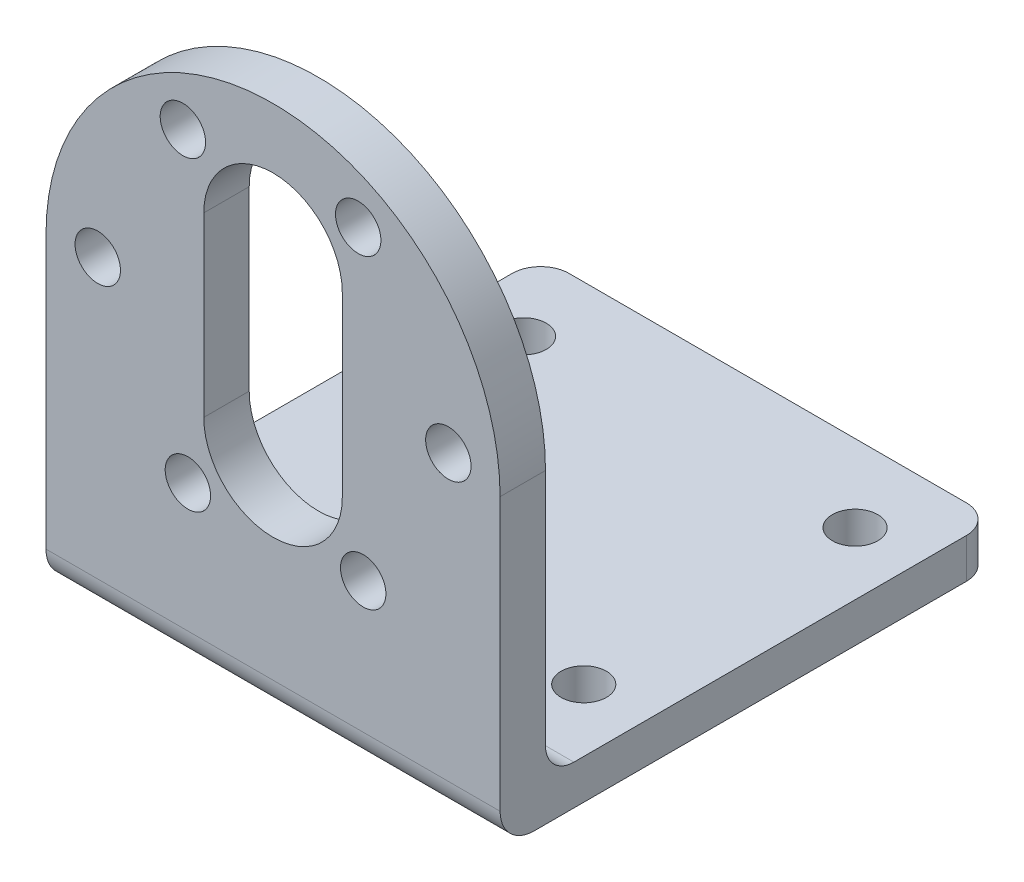
SolidWorks part; units mm, degrees
ref_plane "Front Plane" through (0, 0, 0) normal (0, 0, 1) x (1, 0, 0)
ref_plane "Top Plane" through (0, 0, 0) normal (0, 1, 0) x (1, 0, 0)
ref_plane "Right Plane" through (0, 0, 0) normal (1, 0, 0) x (0, 0, -1)
sketch "Sketch2" plane through (0, 0, 0) normal (1, 0, 0) x (0, 0, -1)
  line L1 (-36.8894, 36.5355) -> (-35.3894, 36.5355)
  line L2 (-36.8894, 36.5355) -> (-36.8894, -2.5345)
  line L3 (-36.8894, -2.5345) -> (-35.3894, -2.5345)
  line L4 (-35.3894, 36.5355) -> (-35.3894, -2.5345)
  line L5 (-36.8894, -2.5345) -> (4.1796, -2.5345)
  line L6 (-36.8894, -2.5345) -> (-36.8894, -1.0345)
  line L7 (-36.8894, -1.0345) -> (4.1796, -1.0345)
  line L8 (4.1796, -2.5345) -> (4.1796, -1.0345)
  dimension "D1" = 1.5
  dimension "D2" = 1.5
  dimension "D3" = 39.07
  dimension "D4" = 41.069
extrude "Boss-Extrude1" add sketch "Sketch2" along normal blind 40 contours L3 L4 L1 L2 | L5 L8 L7 L6
sketch "Sketch3" plane through (0, -1.0345, 0) normal (0, 1, 0) x (1, 0, 0)
  line L0 (40, 4.1796) -> (0, 4.1796) construction
  line L1 (0, -35.3894) -> (0, 4.1796) construction
  line L2 (40, -35.3894) -> (40, 4.1796) construction
  circle A0 centre (4.5, -30.8204) radius 1.65
  circle A1 centre (4.5, -20.8204) radius 1.65
  circle A2 centre (4.5, -10.8204) radius 1.65
  circle A3 centre (4.5, -0.8204) radius 1.65
  circle A4 centre (35.5, -30.8204) radius 1.65
  circle A5 centre (35.5, -20.8204) radius 1.65
  circle A6 centre (35.5, -10.8204) radius 1.65
  circle A7 centre (35.5, -0.8204) radius 1.65
  dimension "D1" = 3.3
  dimension "D2" = 5
  dimension "D3" = 10
  dimension "D4" = 10
  dimension "D5" = 10
  dimension "D6" = 5
  dimension "D7" = 10
  dimension "D8" = 10
  dimension "D9" = 30
  dimension "D10" = 4.5
  dimension "D11" = 4.5
  dimension "D12" = 4.5
  dimension "D13" = 4.5
  dimension "D14" = 4.5
  dimension "D15" = 4.5
extrude "Cut-Extrude1" cut sketch "Sketch3" against normal blind 40
sketch "Sketch4" plane through (0, 0, 35.3894) normal (0, 0, -1) x (-1, 0, 0)
  circle A0 centre (-20, 16.5355) radius 10.5
  circle A1 centre (-20, 16.5355) radius 13
  circle A2 centre (-29.4484, 25.4645) radius 1.65
  circle A3 centre (-10.5516, 7.6065) radius 1.65
  circle A4 centre (-28.929, 7.0871) radius 1.65
  circle A5 centre (-11.071, 25.984) radius 1.65
  arc A6 (-40, 16.5355) -> (0, 16.5355) centre (-20, 16.5355) cw
  line M2 (0, -1.0345) -> (0, 36.5355)
  line M3 (0, 36.5355) -> (-40, 36.5355)
  line M4 (-40, 36.5355) -> (-40, -1.0345)
  dimension "D1" = 21
  dimension "D4" = 26
  dimension "D5" = 3.3
  dimension "D9" = 20
  dimension "D2" = 19.07
  dimension "D3" = 20
  dimension "D6" = 90
  dimension "D7" = 90
  dimension "D8" = 90
  dimension "D10" = 40
extrude "Cut-Extrude2" cut sketch "Sketch4" against normal blind 40 contours A0 | A1 A4 | A1 A4 | A1 A3 | A1 A3 | A6 M4 M3 | A6 M3 M2 | A1 A5 | A1 A5 | A1 A2 | A1 A2
sketch "草图1" plane through (0, 0, 36.8894) normal (0, 0, 1) x (1, 0, 0)
  line L3 (0, 16.5355) -> (0, -2.5345)
  line L4 (0, -2.5345) -> (40, -2.5345)
  line L5 (40, -2.5345) -> (40, 16.5355)
  line L6 (0, 16.5355) -> (0, -2.5345)
  line L7 (0, -2.5345) -> (40, -2.5345)
  line L8 (40, -2.5345) -> (40, 16.5355)
  circle A0 centre (20, 16.5355) radius 10.5 construction
  arc A1 (40, 16.5355) -> (0, 16.5355) centre (20, 16.5355) ccw
  arc A2 (40, 16.5355) -> (0, 16.5355) centre (20, 16.5355) ccw
  circle A3 centre (20, 16.5355) radius 10.5
  circle A4 centre (11.071, 25.984) radius 1.65 construction
  circle A5 centre (29.4484, 25.4645) radius 1.65 construction
  circle A6 centre (28.929, 7.0871) radius 1.65 construction
  circle A7 centre (10.5516, 7.6065) radius 1.65 construction
  circle A8 centre (11.071, 25.984) radius 1.65
  circle A9 centre (29.4484, 25.4645) radius 1.65
  circle A10 centre (28.929, 7.0871) radius 1.65
  circle A11 centre (10.5516, 7.6065) radius 1.65
  dimension "D1" = 0
extrude "凸台-拉伸1" add sketch "草图1" along normal blind 2.5
fillet "圆角1" radius 2.5 1 edges at (20, -1.0345, 35.3894)
sketch "草图2" plane through (0, -2.5345, 0) normal (0, -1, 0) x (1, 0, 0)
  line L1 (40, 39.3894) -> (0, 39.3894)
  line L2 (40, 39.3894) -> (40, -4.1796)
  line L3 (40, -4.1796) -> (0, -4.1796)
  line L4 (0, 39.3894) -> (0, -4.1796)
  circle A0 centre (4.5, 30.8204) radius 1.65
  circle A1 centre (4.5, 20.8204) radius 1.65
  circle A2 centre (4.5, 0.8204) radius 1.65
  circle A3 centre (4.5, 10.8204) radius 1.65
  circle A4 centre (35.5, 30.8204) radius 1.65
  circle A5 centre (35.5, 20.8204) radius 1.65
  circle A6 centre (35.5, 10.8204) radius 1.65
  circle A7 centre (35.5, 0.8204) radius 1.65
extrude "凸台-拉伸2" add sketch "草图2" along normal blind 2
fillet "圆角2" radius 2.5 2 edges at (40, -2.7845, -4.1796) (0, -2.7845, -4.1796)
sketch "草图3" plane through (0, -1.0345, 0) normal (0, 1, 0) x (1, 0, 0)
  circle A0 centre (35.5, -0.8204) radius 1.65 construction
  circle A1 centre (35.5, -10.8204) radius 1.65 construction
  circle A2 centre (35.5, -20.8204) radius 1.65 construction
  circle A3 centre (35.5, -30.8204) radius 1.65 construction
  circle A4 centre (4.5, -0.8204) radius 1.65 construction
  circle A5 centre (4.5, -10.8204) radius 1.65 construction
  circle A6 centre (4.5, -20.8204) radius 1.65 construction
  circle A7 centre (4.5, -30.8204) radius 1.65 construction
  circle A8 centre (35.5, -0.8204) radius 1.65
  circle A9 centre (35.5, -10.8204) radius 1.65
  circle A10 centre (35.5, -20.8204) radius 1.65
  circle A11 centre (35.5, -30.8204) radius 1.65
  circle A12 centre (4.5, -0.8204) radius 1.65
  circle A13 centre (4.5, -10.8204) radius 1.65
  circle A14 centre (4.5, -20.8204) radius 1.65
  circle A15 centre (4.5, -30.8204) radius 1.65
extrude "凸台-拉伸3" add sketch "草图3" against normal up to surface (3.5 mm away) up to face at (20, -4.5345, 11.0042)
sketch "草图4" plane through (0, -1.0345, 0) normal (0, 1, 0) x (1, 0, 0)
  circle A0 centre (34.5, -2.6204) radius 2
  circle A1 centre (34.5, -26.5204) radius 2
  circle A2 centre (5.3, -2.6204) radius 2
  circle A3 centre (5.3, -26.5204) radius 2
extrude "切除-拉伸1" cut sketch "草图4" against normal up to surface (3.5 mm away)
fillet "圆角3" radius 3 1 edges at (20, -4.5345, 39.3894)
sketch "草图5" plane through (0, -4.5345, 0) normal (0, -1, 0) x (1, 0, 0)
  line L0 (0, 39.3894) -> (40, 39.3894) construction
  line L1 (0, 39.3894) -> (40, 39.3894)
  line L2 (40, 35.3894) -> (0, 35.3894) construction
  line L3 (40, 35.3894) -> (0, 35.3894)
  line L4 (0, 39.3894) -> (0, 35.3894)
  line L5 (40, 39.3894) -> (40, 35.3894)
extrude "凸台-拉伸4" add sketch "草图5" against normal blind 27
fillet "圆角4" radius 3 1 edges at (20, -4.5345, 39.3894)
sketch "草图7" plane through (0, 0, 39.3894) normal (0, 0, 1) x (1, 0, 0)
  line L0 (0, 22.4655) -> (40, 22.4655)
  arc A0 (40, 22.4655) -> (0, 22.4655) centre (20, 22.4655) ccw
  point P4 (20, 22.4655)
extrude "凸台-拉伸5" add sketch "草图7" against normal up to surface (4 mm away) up to face at (20, 24.7505, 35.3894)
sketch "草图8" plane through (0, 0, 39.3894) normal (0, 0, 1) x (1, 0, 0)
  line L1 (26.1, 31.0655) -> (26.1, 15.4655)
  line L2 (40, -4.5345) -> (0, -4.5345) construction
  line L3 (40, -1.5345) -> (40, 22.4655) construction
  line L4 (13.9, 15.4655) -> (13.9, 31.0655)
  arc A1 (13.9, 15.4655) -> (26.1, 15.4655) centre (20, 15.4655) ccw
  arc A2 (13.9, 31.0655) -> (26.1, 31.0655) centre (20, 31.0655) cw
  point P0 (13.9, 23.2655)
  point P5 (26.1, 23.2655)
  dimension "D4" = 15.6
  dimension "D5" = 20
  dimension "D1" = 6.1
  dimension "D3" = 6.1
  dimension "D2" = 13.9
extrude "切除-拉伸2" cut sketch "草图8" against normal up to surface (4 mm away) up to face at (20, 16.9655, 35.3894)
sketch "草图9" plane through (0, 0, 39.3894) normal (0, 0, 1) x (1, 0, 0)
  line L0 (13.9, 31.0655) -> (13.9, 15.4655) construction
  line L1 (26.1, 15.4655) -> (26.1, 31.0655) construction
  line L2 (13.9, 31.0655) -> (13.9, 15.4655)
  line L3 (26.1, 15.4655) -> (26.1, 31.0655)
  line L4 (20, 37.1655) -> (20, 9.3655)
  line L5 (12.5, 36.7655) -> (27.5, 36.7655)
  line L6 (12.5, 36.7655) -> (12.5, 9.7655)
  line L7 (12.5, 9.7655) -> (27.5, 9.7655)
  line L8 (27.5, 36.7655) -> (27.5, 9.7655)
  arc A0 (26.1, 31.0655) -> (13.9, 31.0655) centre (20, 31.0655) ccw construction
  arc A1 (13.9, 15.4655) -> (26.1, 15.4655) centre (20, 15.4655) ccw construction
  arc A2 (26.1, 31.0655) -> (13.9, 31.0655) centre (20, 31.0655) ccw
  arc A3 (13.9, 15.4655) -> (26.1, 15.4655) centre (20, 15.4655) ccw
  circle A4 centre (20, 23.2655) radius 15.4434
  circle A5 centre (27.5, 36.7655) radius 2
  circle A6 centre (35.4413, 23.5203) radius 2
  circle A7 centre (27.9413, 10.0203) radius 2
  circle A8 centre (12.5, 9.7655) radius 2
  circle A9 centre (4.5587, 23.0107) radius 2
  circle A10 centre (12.0587, 36.5107) radius 2
  point P27 (20, 23.2655)
  dimension "D6" = 6
  dimension "D7" = 30.8827
  dimension "D8" = 4
  dimension "D1" = 15
  dimension "D2" = 27
  dimension "D3" = 7.5
  dimension "D4" = 27.8
  dimension "D5" = 0.4
sketch "草图10" plane through (0, 0, 39.3894) normal (0, 0, 1) x (1, 0, 0)
  circle A0 centre (12.5, 9.7655) radius 2 construction
  circle A3 centre (27.9413, 10.0203) radius 2 construction
  circle A4 centre (35.4413, 23.5203) radius 2 construction
  circle A5 centre (27.5, 36.7655) radius 2 construction
  circle A6 centre (12.0587, 36.5107) radius 2 construction
  circle A7 centre (4.5587, 23.0107) radius 2 construction
  circle A8 centre (12.5, 9.7655) radius 2
  circle A9 centre (27.9413, 10.0203) radius 2
  circle A10 centre (35.4413, 23.5203) radius 2
  circle A11 centre (27.5, 36.7655) radius 2
  circle A12 centre (12.0587, 36.5107) radius 2
  circle A13 centre (4.5587, 23.0107) radius 2
extrude "切除-拉伸3" cut sketch "草图10" against normal up to surface (4 mm away) up to face at (20, 23.2655, 35.3894)
